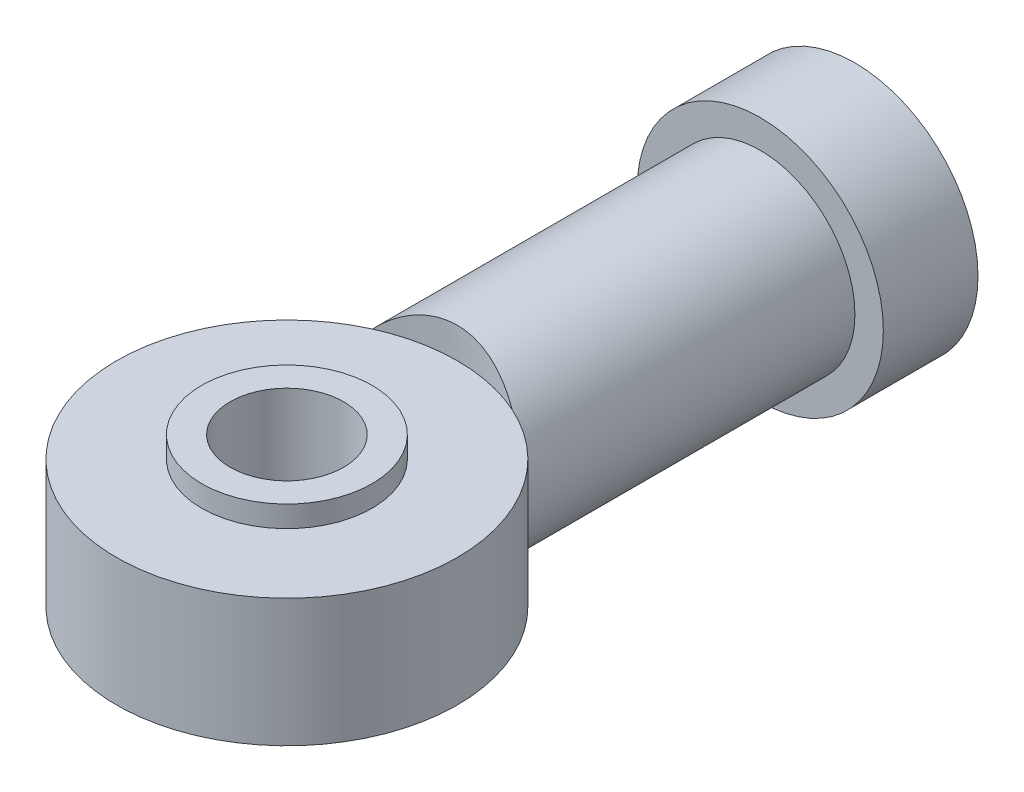
SolidWorks part; units mm, degrees
material "合金钢"
ref_plane "前视基准面" through (0, 0, 0) normal (0, 0, 1) x (1, 0, 0)
ref_plane "上视基准面" through (0, 0, 0) normal (0, 1, 0) x (1, 0, 0)
ref_plane "右视基准面" through (0, 0, 0) normal (1, 0, 0) x (0, 0, -1)
sketch "草图2" plane through (0, 0, 0) normal (0, 0, 1) x (1, 0, 0)
  circle A0 centre (0, 0) radius 6.5
  dimension "D1" = 13
extrude "凸台-拉伸1" add sketch "草图2" along normal blind 5
sketch "草图3" plane through (0, 0, 0) normal (0, 1, 0) x (1, 0, 0)
  circle A0 centre (0, -30) radius 9
  point P2 (0, 0)
  dimension "D1" = 18
  dimension "D2" = 30
extrude "凸台-拉伸2" add sketch "草图3" along normal mid plane 13 separate body
sketch "草图4" plane through (0, 6.5, 0) normal (0, 1, 0) x (1, 0, 0)
  circle A0 centre (0, -30) radius 3
  circle A1 centre (0, -30) radius 9 construction
  dimension "D1" = 6
extrude "切除-拉伸1" cut sketch "草图4" against normal blind 18
sketch "草图7" plane through (0, 0, 5) normal (0, 0, 1) x (1, 0, 0)
  circle A0 centre (0, 0) radius 5
  dimension "D1" = 10
extrude "凸台-拉伸3" add sketch "草图7" along normal up to surface (17.5167 mm away)
sketch "草图8" plane through (0, 6.5, 0) normal (0, 1, 0) x (1, 0, 0)
  circle A0 centre (0, -30) radius 9
  dimension "D1" = 18
extrude "切除-拉伸6" cut sketch "草图8" against normal blind 2
mirror "镜向2" about plane through (0, 0, 0) normal (0, 1, 0) of "切除-拉伸6"
sketch "草图11" plane through (0, 4.5, 0) normal (0, 1, 0) x (1, 0, 0)
  circle A0 centre (0, -30) radius 4.5
  circle A1 centre (0, -30) radius 3 construction
  circle A2 centre (0, -30) radius 9
  dimension "D1" = 9
  dimension "D2" = 18
extrude "切除-拉伸8" cut sketch "草图11" against normal blind 1.125
mirror "镜向3" about plane through (0, 0, 0) normal (0, 1, 0) of "切除-拉伸8"
hole_wizard "M6 螺纹孔3" positions "草图17" profile "草图18" tap size "M6" standard "GB"
sketch "草图17" plane through (0, 0, 0) normal (0, 0, -1) x (-1, 0, 0)
  point P0 (0, 0)
sketch "草图18" plane through (0, 0, 0) normal (1, 0, 0) x (0, 1, 0)
  line L0 (0, 0) -> (0, 18.5022)
  line L1 (0, 18.5022) -> (2.5, 17)
  line L2 (2.5, 17) -> (2.5, 0)
  line L5 (2.5, 0) -> (0, 0)
  line L10 (0, 18.5022) -> (-2.5, 17) construction
  line L11 (0, -6.35) -> (0, 107.95) construction
  dimension "螺纹孔钻头直径" = 5
  dimension "螺纹孔钻头深度" = 17
  dimension "导头角度" = 118
cosmetic thread "孔螺蚊线2" parameters "D1"=14, "D2"=6
